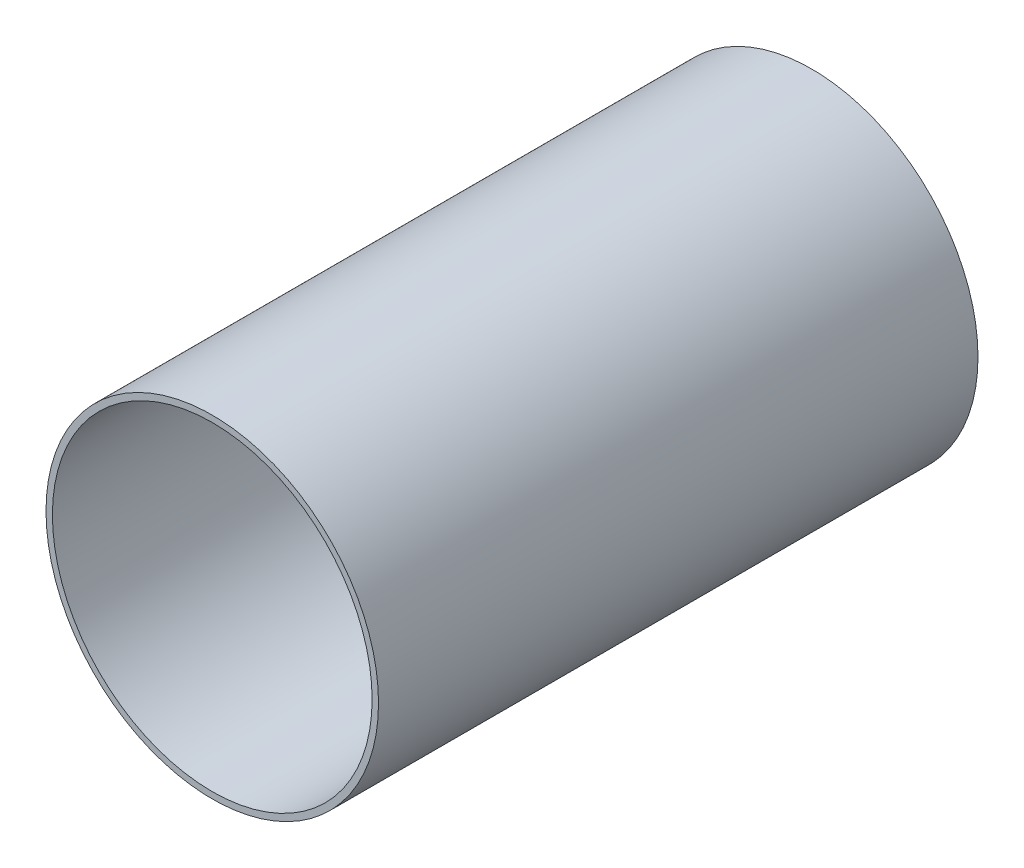
SolidWorks part; units mm, degrees
ref_plane "Front Plane" through (0, 0, 0) normal (0, 0, 1) x (1, 0, 0)
ref_plane "Top Plane" through (0, 0, 0) normal (0, 1, 0) x (1, 0, 0)
ref_plane "Right Plane" through (0, 0, 0) normal (1, 0, 0) x (0, 0, -1)
sketch "Sketch1" plane through (0, 0, 0) normal (0, 0, 1) x (1, 0, 0)
  circle A0 centre (0, 0) radius 0.4
  circle A1 centre (0, 0) radius 0.416
  dimension "D1" = 0.8
  dimension "D2" = 0.832
extrude "Boss-Extrude1" add sketch "Sketch1" along normal blind 1.5
sketch "Sketch2" plane through (0, 0, 0) normal (0, 0, 1) x (1, 0, 0)
  line L0 (0.229, -0.328) -> (0.2386, -0.3408)
  line L1 (-0.2411, -0.339) -> (-0.2319, -0.3259)
  arc A0 (0.229, -0.328) -> (-0.2319, -0.3259) centre (0, 0) cw
  circle A1 centre (0, 0) radius 0.4 construction
  arc A2 (-0.2411, -0.339) -> (0.2386, -0.3408) centre (0, 0) ccw
  circle A3 centre (0, 0) radius 0.416 construction
